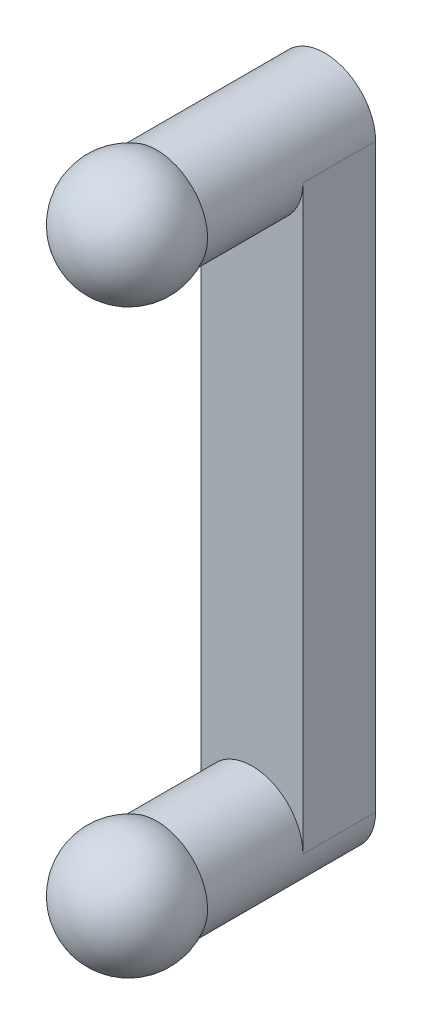
SolidWorks part; units mm, degrees
other "标注1"
sketch "草图3" plane through (-22.25, 4, -10) normal (-0.231, 0.6469, -0.7268) x (-0.9696, -0.2151, 0.1167)
ref_plane "前视基准面" through (0, 0, 0) normal (0, 0, 1) x (1, 0, 0)
ref_plane "上视基准面" through (0, 0, 0) normal (0, 1, 0) x (1, 0, 0)
ref_plane "右视基准面" through (0, 0, 0) normal (1, 0, 0) x (0, 0, -1)
other "Configuration Table"
sketch "草图4" plane through (0, 0, 0) normal (0, 1, 0) x (1, 0, 0)
  line L10 (0, 1.6476) -> (0, -8.5624) construction
  line L11 (-1.4, 0) -> (1.4, 0)
  line L12 (-1.4, 0) -> (-1.4, -7)
  line L13 (-1.4, -7) -> (1.4, -7)
  line L14 (1.4, 0) -> (1.4, -7)
  circle A1 centre (0, -5.4) radius 1.6
  dimension "D1" = 2.8
  dimension "D2" = 7
  dimension "D3" = 3.2
revolve "旋转1" add sketch "草图4" angle 360 about L10
sketch "草图5" plane through (0, 0, 0) normal (0, 0, -1) x (-1, 0, 0)
  line L1 (-1.4, 0) -> (1.4, 0)
  line L2 (-1.4, 0) -> (-1.4, 8)
  line L3 (-1.4, 8) -> (1.4, 8)
  line L4 (1.4, 0) -> (1.4, 8)
  circle A0 centre (0, 0) radius 1.4 construction
  dimension "D1" = 8
extrude "凸台-拉伸1" add sketch "草图5" against normal blind 2
mirror "镜向1" about plane through (1.4, 8, 2) normal (0, 1, 0) of bodies 246
ref_plane "基准面1" through (0, -1.4, 0) normal (0, -1, 0) x (-1, 0, 0)
ref_plane "基准面2" through (0, 17.4, 0) normal (0, 1, 0) x (1, 0, 0)
